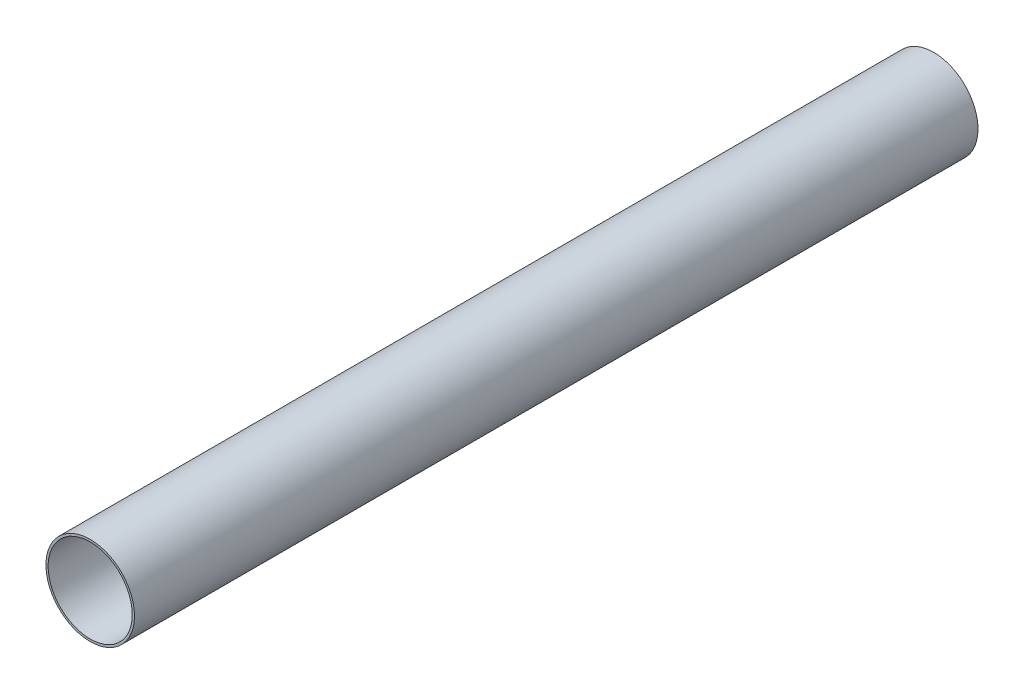
SolidWorks part; units mm, degrees
material "Q235A"
ref_plane "前视" through (0, 0, 0) normal (0, 0, 1) x (1, 0, 0)
ref_plane "上视" through (0, 0, 0) normal (0, 1, 0) x (1, 0, 0)
ref_plane "右视" through (0, 0, 0) normal (1, 0, 0) x (0, 0, -1)
sketch "草图1" plane through (0, 0, 0) normal (0, 0, 1) x (1, 0, 0)
  circle A0 centre (0, 0) radius 60
  circle A1 centre (0, 0) radius 57
  dimension "D1" = 114
  dimension "D2" = 120
extrude "凸台-拉伸1" add sketch "草图1" along normal blind 1143
